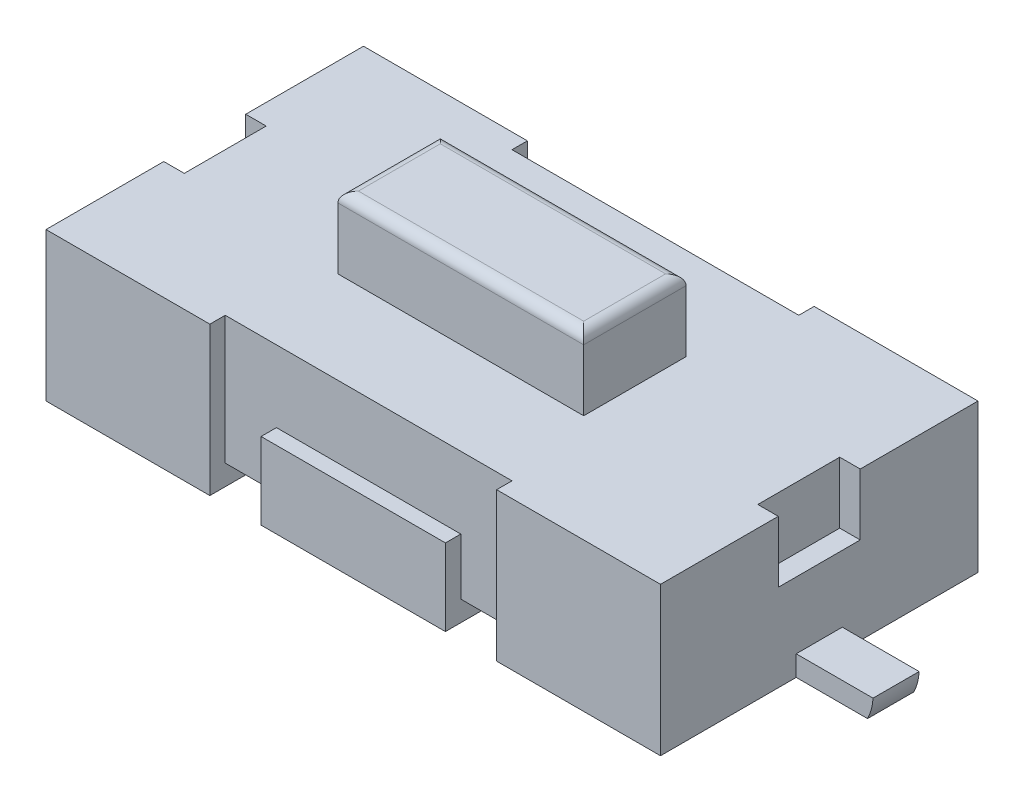
SolidWorks part; units mm, degrees
material "ABS"
ref_plane "Front Plane" through (0, 0, 0) normal (0, 0, 1) x (1, 0, 0)
ref_plane "Top Plane" through (0, 0, 0) normal (0, 1, 0) x (1, 0, 0)
ref_plane "Right Plane" through (0, 0, 0) normal (1, 0, 0) x (0, 0, -1)
sketch "Sketch1" plane through (0, 0, 0) normal (0, 1, 0) x (1, 0, 0)
  line L0 (-55, 0) -> (55, 0) construction
  line L1 (-3, 1.55) -> (3, 1.55)
  line L2 (-3, 1.55) -> (-3, -1.55)
  line L3 (-3, -1.55) -> (3, -1.55)
  line L4 (3, 1.55) -> (3, -1.55)
  line L5 (0, -55) -> (0, 55) construction
  dimension "D1" = 6
  dimension "D2" = 3.1
  dimension "D3" = 1.55
  dimension "D4" = 3
extrude "Boss-Extrude1" add sketch "Sketch1" along normal blind 1.45
sketch "Sketch2" plane through (0, 1.45, 0) normal (0, 1, 0) x (1, 0, 0)
  line L0 (0, 1.55) -> (0, -1.55) construction
  line L1 (3, 1.55) -> (-3, 1.55) construction
  line L2 (-3, -1.55) -> (3, -1.55) construction
  line L4 (-1.2, -0.5) -> (1.2, -0.5)
  line L5 (-1.2, -0.5) -> (-1.2, 0.5)
  line L6 (-1.2, 0.5) -> (1.2, 0.5)
  line L7 (1.2, -0.5) -> (1.2, 0.5)
  line L8 (-1.2, -0.5) -> (1.2, 0.5) construction
  line L9 (-1.2, 0.5) -> (1.2, -0.5) construction
  point P7 (0, 0)
  dimension "D1" = 2.4
  dimension "D2" = 1
extrude "Boss-Extrude2" add sketch "Sketch2" along normal blind 0.7 separate body
fillet "Fillet1" radius 0.1 4 edges at (1.2, 2.15, 0) (0, 2.15, -0.5) (-1.2, 2.15, 0) (0, 2.15, 0.5)
sketch "Sketch3" plane through (-3, 0, 0) normal (-1, 0, 0) x (0, 0, 1)
  line L0 (-1.55, 1.45) -> (1.55, 1.45) construction
  line L1 (-0.4, 1.45) -> (0.4, 1.45)
  line L2 (-0.4, 1.45) -> (-0.4, 0.85)
  line L3 (-0.4, 0.85) -> (0.4, 0.85)
  line L4 (0.4, 1.45) -> (0.4, 0.85)
  line L5 (0, -55) -> (0, 55) construction
  dimension "D1" = 0.8
  dimension "D2" = 0.4
  dimension "D3" = 0.6
extrude "Cut-Extrude1" cut sketch "Sketch3" against normal blind 0.2
sketch "Sketch4" plane through (3, 0, 0) normal (1, 0, 0) x (0, 0, -1)
  line L1 (-0.4, 1.45) -> (0.4, 1.45)
  line L2 (-0.4, 1.45) -> (-0.4, 0.85)
  line L3 (-0.4, 0.85) -> (0.4, 0.85)
  line L4 (0.4, 1.45) -> (0.4, 0.85)
extrude "Cut-Extrude2" cut sketch "Sketch4" against normal blind 0.2
sketch "Sketch5" plane through (0, 0, 1.55) normal (0, 0, 1) x (1, 0, 0)
  line L0 (-3, 1.45) -> (3, 1.45) construction
  line L1 (-1.4, 1.45) -> (1.4, 1.45)
  line L2 (-1.4, 1.45) -> (-1.4, 0)
  line L3 (-0.9, 0.75) -> (0.9, 0.75)
  line L4 (1.4, 1.45) -> (1.4, 0)
  line L5 (0.9, 0.75) -> (0.9, 0)
  line L6 (55, 0) -> (-55, 0) construction
  line L7 (-1.4, 0) -> (-0.9, 0)
  line L8 (-0.9, 0) -> (-0.9, 0.75)
  line L9 (0.9, 0) -> (1.4, 0)
  line L10 (0, -55) -> (0, 55) construction
  dimension "D1" = 0.7
  dimension "D2" = 2.8
  dimension "D3" = 1.4
  dimension "D4" = 0.5
extrude "Cut-Extrude3" cut sketch "Sketch5" against normal blind 0.15
sketch "Sketch6" plane through (0, 0, -1.55) normal (0, 0, -1) x (-1, 0, 0)
  line L0 (-1.4, 1.45) -> (1.4, 1.45)
  line L1 (1.4, 1.45) -> (1.4, 0)
  line L2 (1.4, 0) -> (0.9, 0)
  line L3 (0.9, 0) -> (0.9, 0.75)
  line L4 (0.9, 0.75) -> (-0.9, 0.75)
  line L5 (-0.9, 0.75) -> (-0.9, 0)
  line L6 (-0.9, 0) -> (-1.4, 0)
  line L7 (-1.4, 0) -> (-1.4, 1.45)
extrude "Cut-Extrude4" cut sketch "Sketch6" against normal blind 0.15
sketch "Sketch7" plane through (0, 0, 0) normal (0, -1, 0) x (1, 0, 0)
  line L0 (-0.9, -1.4) -> (-0.9, -1.55) construction
  line L1 (-1.4, 1.4) -> (-0.9, 1.4)
  line L2 (-1.4, 1.4) -> (-1.4, 0.9)
  line L3 (-1.4, 0.9) -> (-0.9, 0.9)
  line L4 (-0.9, 1.4) -> (-0.9, 0.9)
  line L5 (0.9, 1.4) -> (1.4, 1.4)
  line L6 (0.9, 1.4) -> (0.9, 0.9)
  line L7 (0.9, 0.9) -> (1.4, 0.9)
  line L8 (1.4, 1.4) -> (1.4, 0.9)
  line L9 (0.9, -1.4) -> (1.4, -1.4)
  line L10 (0.9, -1.4) -> (0.9, -0.9)
  line L11 (0.9, -0.9) -> (1.4, -0.9)
  line L12 (1.4, -1.4) -> (1.4, -0.9)
  line L13 (-1.4, -1.4) -> (-0.9, -1.4)
  line L14 (-1.4, -1.4) -> (-1.4, -0.9)
  line L15 (-1.4, -0.9) -> (-0.9, -0.9)
  line L16 (-0.9, -1.4) -> (-0.9, -0.9)
  line L17 (1.4, -1.4) -> (1.4, -1.55) construction
  dimension "D1" = 1.8
extrude "Cut-Extrude5" cut sketch "Sketch7" against normal blind 0.2
sketch "Sketch8" plane through (0, 0, 0) normal (0, 0, 1) x (1, 0, 0)
  line L0 (-3.6967, 0) -> (3.6967, 0)
  line L1 (1.705, 0) -> (-1.705, 0) construction
  line L4 (-3.75, 0.2) -> (3.75, 0.2)
  line L6 (0, 0) -> (0, 2.05) construction
  line L7 (1.2, 2.05) -> (-1.2, 2.05) construction
  arc A0 (3.6967, 0) -> (3.75, 0.2) centre (3.2507, 0.226) ccw
  arc A1 (-3.6967, 0) -> (-3.75, 0.2) centre (-3.2507, 0.226) cw
  point P8 (-3.476, 0)
  point P15 (0.4501, 2.05)
  dimension "D1" = 0.5
  dimension "D2" = 0.2
  dimension "D3" = 7.5
extrude "Boss-Extrude4" add sketch "Sketch8" along normal mid plane 0.45 separate body
sketch "Sketch9" plane through (0, 0, 0) normal (0, 1, 0) x (1, 0, 0)
  line L0 (-1.1825, 0) -> (1.1825, 0) construction
  line L1 (-2.6, 1.05) -> (2.6, 1.05)
  line L2 (-2.6, 1.05) -> (-2.6, -1.05)
  line L3 (-2.6, -1.05) -> (2.6, -1.05)
  line L4 (2.6, 1.05) -> (2.6, -1.05)
  line L5 (0, -1.1825) -> (0, 1.1825) construction
  dimension "D1" = 2.1
  dimension "D2" = 1.05
  dimension "D3" = 5.2
  dimension "D4" = 2.6
extrude "Boss-Extrude5" add sketch "Sketch9" along normal blind 0.025
